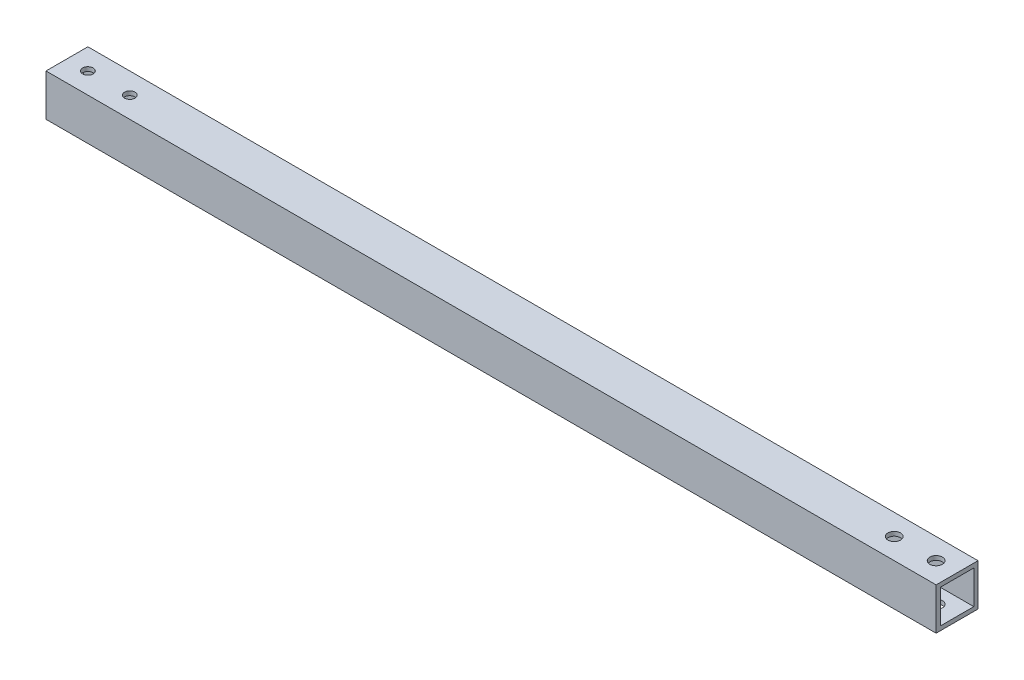
SolidWorks part; units mm, degrees
material "1060 Alloy"
ref_plane "Front Plane" through (0, 0, 0) normal (0, 0, 1) x (1, 0, 0)
ref_plane "Top Plane" through (0, 0, 0) normal (0, 1, 0) x (1, 0, 0)
ref_plane "Right Plane" through (0, 0, 0) normal (1, 0, 0) x (0, 0, -1)
sketch "Sketch1" plane through (0, 0, 0) normal (1, 0, 0) x (0, 0, -1)
  line L0 (8, 8) -> (-8, 8)
  line L1 (-8, 8) -> (-8, -8)
  line L2 (0, 0) -> (0, 27.1676) construction
  line L3 (0, 0) -> (-28.5263, 0) construction
  line L4 (8, 8) -> (8, -8)
  line L5 (8, -8) -> (-8, -8)
  line L7 (-10, 10) -> (10, 10)
  line L8 (-10, 10) -> (-10, -10)
  line L9 (-10, -10) -> (10, -10)
  line L10 (10, 10) -> (10, -10)
  point P8 (0, 8)
  point P11 (8, 0)
  point P12 (-8, 0)
  dimension "D1" = 16
  dimension "D2" = 20
  dimension "D3" = 10
  dimension "D4" = 10
extrude "Boss-Extrude1" add sketch "Sketch1" along normal mid plane 425
sketch "Sketch2" plane through (0, 10, 0) normal (0, 1, 0) x (1, 0, 0)
  line L0 (212.5, 10) -> (212.5, -10) construction
  line L1 (0, 0) -> (221.7004, 0) construction
  circle A0 centre (182.5, 0) radius 3
  circle A1 centre (202.5, 0) radius 3
  dimension "D1" = 6
  dimension "D2" = 6
  dimension "D3" = 20
  dimension "D4" = 10
extrude "Cut-Extrude1" cut sketch "Sketch2" against normal through all
sketch "Sketch3" plane through (0, 10, 0) normal (0, 1, 0) x (1, 0, 0)
  line L0 (0, 0) -> (-231.6707, 0) construction
  line L1 (-212.5, -10) -> (-212.5, 10) construction
  circle A0 centre (-202.5, 0) radius 2.5
  circle A1 centre (-182.5, 0) radius 2.5
  dimension "D1" = 5
  dimension "D2" = 5
  dimension "D3" = 20
  dimension "D4" = 10
extrude "Cut-Extrude2" cut sketch "Sketch3" against normal through all
